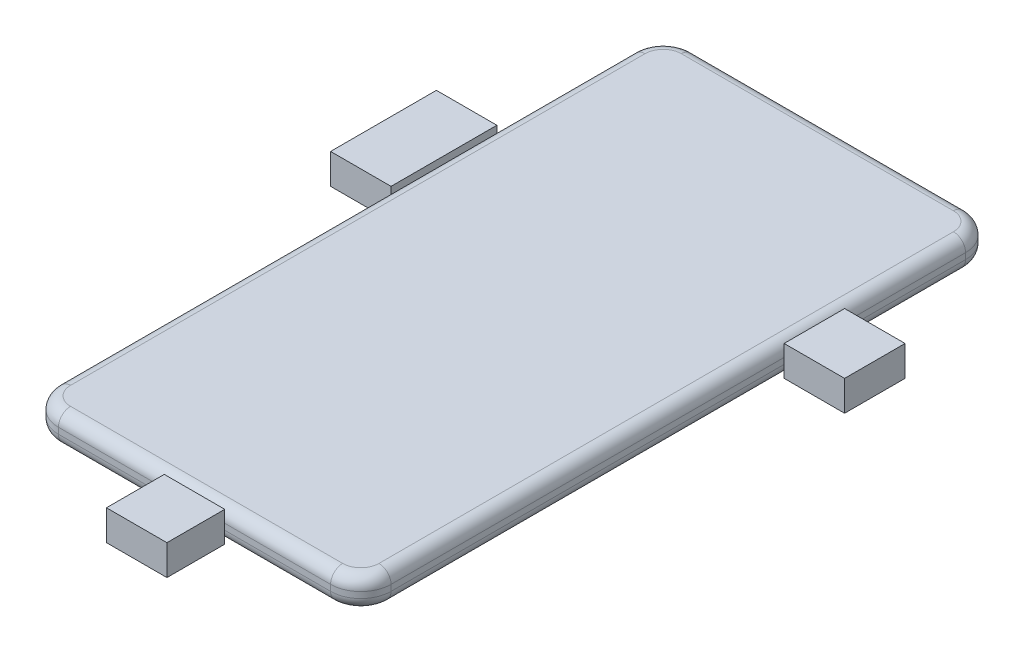
SolidWorks part; units mm, degrees
ref_plane "Front Plane" through (0, 0, 0) normal (0, 0, 1) x (1, 0, 0)
ref_plane "Top Plane" through (0, 0, 0) normal (0, 1, 0) x (1, 0, 0)
ref_plane "Right Plane" through (0, 0, 0) normal (1, 0, 0) x (0, 0, -1)
sketch "Sketch1" plane through (0, 0, 0) normal (0, 1, 0) x (1, 0, 0)
  line L1 (0, 0) -> (69.85, 0)
  line L2 (0, 0) -> (0, 133.35)
  line L3 (0, 133.35) -> (69.85, 133.35)
  line L4 (69.85, 0) -> (69.85, 133.35)
  dimension "D1" = 69.85
  dimension "D2" = 133.35
extrude "Boss-Extrude1" add sketch "Sketch1" along normal blind 6.35
fillet "Fillet2" radius 6.35 4 edges at (0, 3.175, -133.35) (69.85, 3.175, -133.35) (0, 3.175, 0) (69.85, 3.175, 0)
fillet "Fillet3" radius 2.54 16 edges at (67.9901, 0, -1.8599) (34.925, 0, 0) (1.8599, 0, -1.8599) (0, 0, -66.675) (1.8599, 0, -131.4901) (34.925, 0, -133.35) (67.9901, 0, -131.4901) (67.9901, 6.35, -1.8599) (34.925, 6.35, 0) (1.8599, 6.35, -1.8599) (0, 6.35, -66.675) (1.8599, 6.35, -131.4901) (34.925, 6.35, -133.35) (67.9901, 6.35, -131.4901) (69.85, 0, -66.675) (69.85, 6.35, -66.675)
sketch "Sketch2" plane through (0, 0, 0) normal (0, 1, 0) x (1, 0, 0)
  line L0 (6.35, 133.35) -> (63.5, 133.35) construction
  line L1 (69.85, 101.6) -> (82.55, 101.6)
  line L2 (69.85, 101.6) -> (69.85, 88.9)
  line L3 (69.85, 88.9) -> (82.55, 88.9)
  line L4 (82.55, 101.6) -> (82.55, 88.9)
  line L5 (0, 98.425) -> (-12.7, 98.425)
  line L6 (0, 98.425) -> (0, 76.2)
  line L7 (0, 76.2) -> (-12.7, 76.2)
  line L8 (-12.7, 98.425) -> (-12.7, 76.2)
  line L9 (0, 6.35) -> (0, 127) construction
  line L10 (69.85, 127) -> (69.85, 6.35) construction
  dimension "D1" = 31.75
  dimension "D2" = 44.45
  dimension "D3" = 57.15
  dimension "D4" = 34.925
  dimension "D5" = 12.7
  dimension "D6" = 12.7
extrude "buttons" add sketch "Sketch2" along normal blind 6.35 separate body
sketch "Sketch3" plane through (0, 0, 0) normal (0, -1, 0) x (1, 0, 0)
  line L0 (63.5, -133.35) -> (6.35, -133.35) construction
  line L1 (12.7, -107.95) -> (57.15, -107.95)
  line L2 (12.7, -107.95) -> (12.7, -127)
  line L3 (12.7, -127) -> (57.15, -127)
  line L4 (57.15, -107.95) -> (57.15, -127)
  line L5 (69.85, -6.35) -> (69.85, -127) construction
  line L6 (0, -127) -> (0, -6.35) construction
  dimension "D1" = 25.4
  dimension "D2" = 19.05
  dimension "D3" = 12.7
  dimension "D4" = 12.7
extrude "camera" add sketch "Sketch3" along normal blind 6.35 separate body
sketch "Sketch4" plane through (0, 0, 0) normal (0, 1, 0) x (1, 0, 0)
  line L0 (63.5, 0) -> (6.35, 0) construction
  line L1 (28.575, -12.1416) -> (41.275, -12.1416)
  line L2 (28.575, -12.1416) -> (28.575, 0)
  line L3 (28.575, 0) -> (41.275, 0)
  line L4 (41.275, -12.1416) -> (41.275, 0)
  line L5 (69.85, 127) -> (69.85, 6.35) construction
  dimension "D1" = 28.575
  dimension "D2" = 12.7
extrude "USB" add sketch "Sketch4" along normal blind 6.35 separate body
